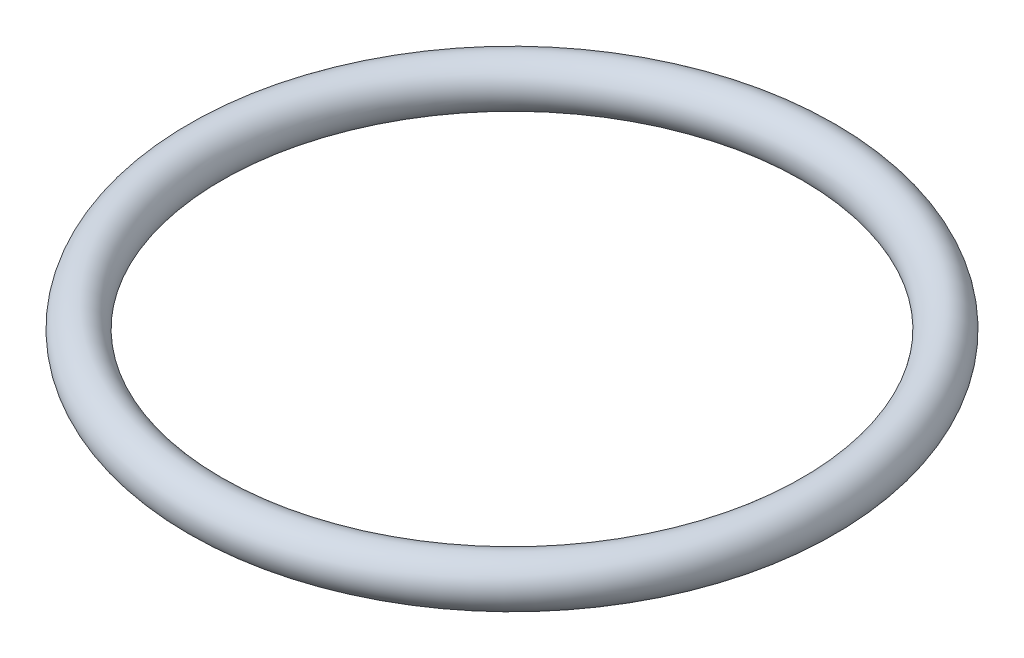
SolidWorks part; units mm, degrees
ref_plane "前视基准面" through (0, 0, 0) normal (0, 0, 1) x (1, 0, 0)
ref_plane "上视基准面" through (0, 0, 0) normal (0, 1, 0) x (1, 0, 0)
ref_plane "右视基准面" through (0, 0, 0) normal (1, 0, 0) x (0, 0, -1)
sketch "草图1" plane through (0, 0, 0) normal (0, 0, 1) x (1, 0, 0)
  line L0 (0, 0) -> (0, 30.274) construction
  circle A0 centre (23.625, 0) radius 1.775
  dimension "D1" = 3.55
  dimension "D2" = 23.625
revolve "旋转1" add sketch "草图1" angle 360 about L0
